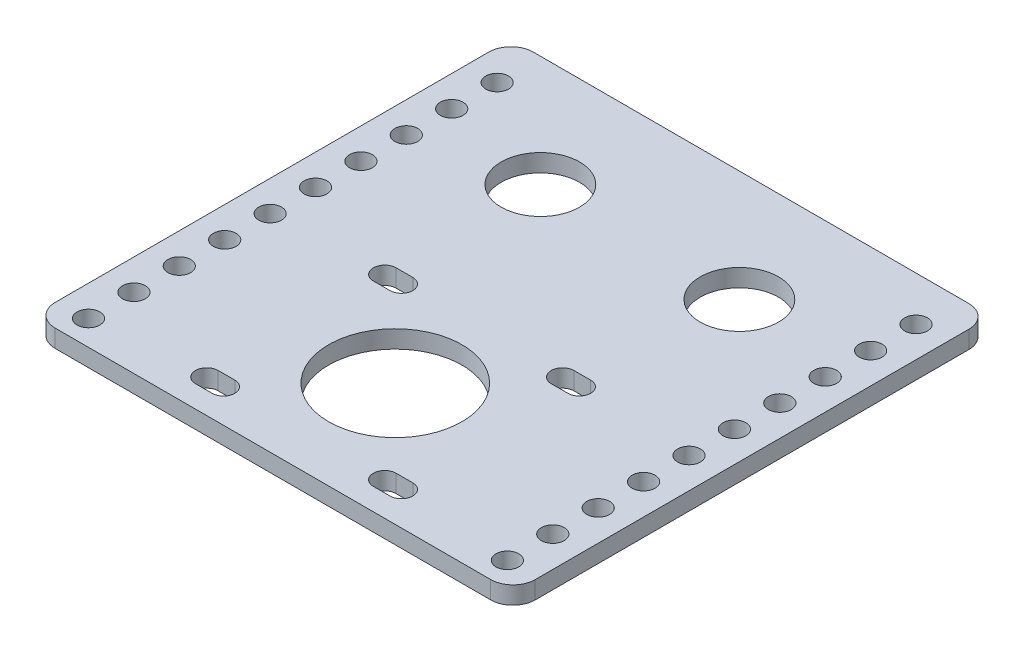
SolidWorks part; units mm, degrees
ref_plane "Front Plane" through (0, 0, 0) normal (0, 0, 1) x (1, 0, 0)
ref_plane "Top Plane" through (0, 0, 0) normal (0, 1, 0) x (1, 0, 0)
ref_plane "Right Plane" through (0, 0, 0) normal (1, 0, 0) x (0, 0, -1)
sketch "Sketch1" plane through (0, 0, 0) normal (0, 1, 0) x (1, 0, 0)
  line L0 (0, 0) -> (0, -50000) construction
  line L1 (-43.175, 43) -> (43.175, 43)
  line L2 (-43.175, 43) -> (-43.175, -43)
  line L3 (-43.175, -43) -> (43.175, -43)
  line L4 (43.175, 43) -> (43.175, -43)
  line L5 (-43.175, 43) -> (43.175, -43) construction
  line L6 (-43.175, -43) -> (43.175, 43) construction
  line L7 (37.675, 1.2802) -> (37.675, -49998.7198) construction
  line L8 (26.7767, 35) -> (-49973.2233, 35) construction
  circle A0 centre (37.675, 35) radius 2.05
  circle A1 centre (37.675, 26.8327) radius 2.05
  circle A2 centre (37.675, 18.6653) radius 2.05
  circle A3 centre (37.675, 10.498) radius 2.05
  circle A4 centre (37.675, 2.3306) radius 2.05
  circle A5 centre (37.675, -5.8367) radius 2.05
  circle A6 centre (37.675, -14.004) radius 2.05
  circle A7 centre (37.675, -22.1714) radius 2.05
  circle A8 centre (37.675, -30.3387) radius 2.05
  circle A9 centre (37.675, -38.506) radius 2.05
  circle A10 centre (-37.675, -38.506) radius 2.05
  circle A11 centre (-37.675, -30.3387) radius 2.05
  circle A12 centre (-37.675, -22.1714) radius 2.05
  circle A13 centre (-37.675, -14.004) radius 2.05
  circle A14 centre (-37.675, -5.8367) radius 2.05
  circle A15 centre (-37.675, 2.3306) radius 2.05
  circle A16 centre (-37.675, 10.498) radius 2.05
  circle A17 centre (-37.675, 18.6653) radius 2.05
  circle A18 centre (-37.675, 26.8327) radius 2.05
  circle A19 centre (-37.675, 35) radius 2.05
  point P0 (0, 0)
  dimension "D5" = 4.1
  dimension "D1" = 86
  dimension "D2" = 86.35
  dimension "D3" = 5.5
  dimension "D4" = 8
  dimension "D6" = 10
extrude "Boss-Extrude1" add sketch "Sketch1" along normal blind 3.175
fillet "Fillet1" radius 4 4 edges at (-43.175, 1.5875, -43) (43.175, 1.5875, -43) (43.175, 1.5875, 43) (-43.175, 1.5875, 43)
sketch "Sketch2" plane through (0, 3.175, 0) normal (0, 1, 0) x (1, 0, 0)
  line L0 (0, 0) -> (0, -50000) construction
  line L1 (0, 0) -> (50000, 0) construction
  line L2 (20.2816, 23) -> (50020.2816, 23) construction
  line L3 (39.175, 43) -> (-39.175, 43) construction
  line L4 (-17.6916, -13.7951) -> (0.2084, 30.1984) construction
  line L5 (35.5916, 15.8016) -> (17.6916, -28.1918) construction
  line L6 (0, -20.9934) -> (50000, -20.9934) construction
  line L7 (-16, -4.9934) -> (16, -4.9934) construction
  line L8 (-16, -4.9934) -> (-16, -36.9934) construction
  line L9 (-16, -36.9934) -> (16, -36.9934) construction
  line L10 (16, -4.9934) -> (16, -36.9934) construction
  line L11 (-16, -4.9934) -> (16, -36.9934) construction
  line L12 (-16, -36.9934) -> (16, -4.9934) construction
  line L13 (-10.05, -30.9934) -> (30.25, -30.9934) construction
  line L14 (-10.05, -30.9934) -> (-10.05, -10.9934) construction
  line L15 (-10.05, -10.9934) -> (30.25, -10.9934) construction
  line L16 (30.25, -30.9934) -> (30.25, -10.9934) construction
  line L17 (-10.05, -30.9934) -> (30.25, -10.9934) construction
  line L18 (-10.05, -10.9934) -> (30.25, -30.9934) construction
  line L19 (0, -10.9934) -> (0, -30.9934) construction
  line L20 (-17.9, -7.0434) -> (-14.9, -7.0434)
  line L21 (41.6, -0.9934) -> (-21.4, -0.9934) construction
  line L22 (41.6, -0.9934) -> (41.6, -40.9934) construction
  line L23 (41.6, -40.9934) -> (-21.4, -40.9934) construction
  line L24 (-21.4, -0.9934) -> (-21.4, -40.9934) construction
  line L25 (41.6, -0.9934) -> (-21.4, -40.9934) construction
  line L26 (41.6, -40.9934) -> (-21.4, -0.9934) construction
  line L27 (38.1, -4.9934) -> (-17.9, -4.9934) construction
  line L28 (38.1, -4.9934) -> (38.1, -36.9934) construction
  line L29 (38.1, -36.9934) -> (-17.9, -36.9934) construction
  line L30 (-17.9, -4.9934) -> (-17.9, -36.9934) construction
  line L31 (38.1, -4.9934) -> (-17.9, -36.9934) construction
  line L32 (38.1, -36.9934) -> (-17.9, -4.9934) construction
  line L33 (-14.9, -2.9434) -> (-17.9, -2.9434)
  line L34 (-6.9, -2.9434) -> (-9.9, -2.9434) construction
  line L35 (-9.9, -7.0434) -> (-6.9, -7.0434) construction
  line L36 (1.1, -2.9434) -> (-1.9, -2.9434) construction
  line L37 (-1.9, -7.0434) -> (1.1, -7.0434) construction
  line L38 (9.1, -2.9434) -> (6.1, -2.9434) construction
  line L39 (6.1, -7.0434) -> (9.1, -7.0434) construction
  line L40 (17.1, -2.9434) -> (14.1, -2.9434)
  line L41 (14.1, -7.0434) -> (17.1, -7.0434)
  line L42 (25.1, -2.9434) -> (22.1, -2.9434) construction
  line L43 (22.1, -7.0434) -> (25.1, -7.0434) construction
  line L44 (33.1, -2.9434) -> (30.1, -2.9434) construction
  line L45 (30.1, -7.0434) -> (33.1, -7.0434) construction
  line L46 (-14.9, -7.0434) -> (-6.9, -7.0434) construction
  line L47 (30.1, -34.9434) -> (33.1, -34.9434) construction
  line L48 (33.1, -39.0434) -> (30.1, -39.0434) construction
  line L49 (14.1, -34.9434) -> (17.1, -34.9434)
  line L50 (17.1, -39.0434) -> (14.1, -39.0434)
  line L51 (-17.9, -34.9434) -> (-14.9, -34.9434)
  line L52 (-14.9, -39.0434) -> (-17.9, -39.0434)
  circle A1 centre (-17.9, 23) radius 18 construction
  circle A3 centre (0, -20.9934) radius 19.1 construction
  circle A4 centre (17.9, 23) radius 19.1 construction
  arc A6 (-17.6916, -13.7951) -> (17.6916, -28.1918) centre (0, -20.9934) ccw construction
  arc A7 (0.2084, 30.1984) -> (35.5916, 15.8016) centre (17.9, 23) cw construction
  circle A8 centre (-17.9, 23) radius 7.05
  circle A9 centre (17.9, 23) radius 7.05
  circle A11 centre (-16, -4.9934) radius 2.05 construction
  circle A12 centre (16, -4.9934) radius 2.05 construction
  circle A13 centre (16, -36.9934) radius 2.05 construction
  circle A14 centre (-16, -36.9934) radius 2.05 construction
  circle A15 centre (0, -20.9934) radius 12
  arc A16 (-17.9, -2.9434) -> (-17.9, -7.0434) centre (-17.9, -4.9934) ccw
  circle A17 centre (38.1, -4.9934) radius 2.05 construction
  circle A18 centre (-17.9, -36.9934) radius 2.05 construction
  circle A19 centre (38.1, -36.9934) radius 2.05 construction
  arc A21 (-14.9, -7.0434) -> (-14.9, -2.9434) centre (-14.9, -4.9934) ccw
  arc A22 (-6.9, -7.0434) -> (-6.9, -2.9434) centre (-6.9, -4.9934) ccw construction
  arc A23 (-9.9, -2.9434) -> (-9.9, -7.0434) centre (-9.9, -4.9934) ccw construction
  arc A24 (1.1, -7.0434) -> (1.1, -2.9434) centre (1.1, -4.9934) ccw construction
  arc A25 (-1.9, -2.9434) -> (-1.9, -7.0434) centre (-1.9, -4.9934) ccw construction
  arc A26 (9.1, -7.0434) -> (9.1, -2.9434) centre (9.1, -4.9934) ccw construction
  arc A27 (6.1, -2.9434) -> (6.1, -7.0434) centre (6.1, -4.9934) ccw construction
  arc A28 (17.1, -7.0434) -> (17.1, -2.9434) centre (17.1, -4.9934) ccw
  arc A29 (14.1, -2.9434) -> (14.1, -7.0434) centre (14.1, -4.9934) ccw
  arc A30 (25.1, -7.0434) -> (25.1, -2.9434) centre (25.1, -4.9934) ccw construction
  arc A31 (22.1, -2.9434) -> (22.1, -7.0434) centre (22.1, -4.9934) ccw construction
  arc A32 (33.1, -7.0434) -> (33.1, -2.9434) centre (33.1, -4.9934) ccw construction
  arc A33 (30.1, -2.9434) -> (30.1, -7.0434) centre (30.1, -4.9934) ccw construction
  arc A34 (33.1, -34.9434) -> (33.1, -39.0434) centre (33.1, -36.9934) cw construction
  arc A35 (30.1, -39.0434) -> (30.1, -34.9434) centre (30.1, -36.9934) cw construction
  arc A36 (17.1, -34.9434) -> (17.1, -39.0434) centre (17.1, -36.9934) cw
  arc A37 (14.1, -39.0434) -> (14.1, -34.9434) centre (14.1, -36.9934) cw
  arc A38 (-17.9, -39.0434) -> (-17.9, -34.9434) centre (-17.9, -36.9934) cw
  arc A39 (-14.9, -34.9434) -> (-14.9, -39.0434) centre (-14.9, -36.9934) cw
  point P31 (10.1, -20.9934)
  point P36 (10.1, -20.9934)
  point P45 (10.1, -20.9934)
  dimension "D1" = 38.2
  dimension "D4" = 36
  dimension "D7" = 14.1
  dimension "D10" = 4.1
  dimension "D11" = 24
  dimension "D19" = 4.1
  dimension "D21" = 2.05
  dimension "D2" = 35.8
  dimension "D3" = 17.9
  dimension "D5" = 20
  dimension "D8" = 32
  dimension "D9" = 32
  dimension "D12" = 40.3
  dimension "D13" = 20
  dimension "D14" = 10.05
  dimension "D15" = 63
  dimension "D16" = 40
  dimension "D17" = 56
  dimension "D18" = 32
  dimension "D20" = 3
  dimension "D23" = 8
  dimension "D22" = 7
extrude "Cut-Extrude1" cut sketch "Sketch2" against normal blind 3.18
equation "\"w\"= 86.35mm"
equation "\"h\"= 86mm"
equation "\"D1@Sketch1\"=\"h\""
equation "\"D2@Sketch1\"=\"w\""
equation "\"sh\"= 4.1mm"
equation "\"D5@Sketch1\"=\"sh\""
equation "\"thick\"= 3.175mm"
equation "\"D1@Boss-Extrude1\"=\"thick\""
equation "\"ptich diameter\"= 38.2mm"
equation "\"gearC2C\"= 35.8mm"
equation "\"D1@Sketch2\"=\"ptich diameter\""
equation "\"D2@Sketch2\"=\"gearC2C\""
equation "\"D3@Sketch2\"=\"gearC2C\"/2"
equation "\"45 Tooth Hub-Mount Gear\" = 36mm"
equation "\"D4@Sketch2\"=\"45 Tooth Hub-Mount Gear\""
equation "\"pathLength\"= 215mm"
equation "\"D6@Sketch2\"=\"pathLength\""
equation "\"bearingID\"= 14.1mm"
equation "\"D7@Sketch2\"=\"bearingID\""
equation "\"pillowMountHoles\"= 32mm"
equation "\"D8@Sketch2\"=\"pillowMountHoles\""
equation "\"D9@Sketch2\"=\"pillowMountHoles\""
equation "\"D10@Sketch2\"=\"sh\""
equation "\"servow\"= 40.3mm"
equation "\"servoh\"= 20mm"
equation "\"D12@Sketch2\"=\"servow\""
equation "\"D13@Sketch2\"=\"servoh\""
equation "\"servoMountW\"= 63mm"
equation "\"servoMountH\"= 40mm"
equation "\"D15@Sketch2\"=\"servoMountW\""
equation "\"D16@Sketch2\"=\"servoMountH\""
equation "\"servoMountHoleW\"= \"servoMountW\" - 7mm"
equation "\"servoMountHoleH\"= \"servoMountH\" - 8mm"
equation "\"D17@Sketch2\"=\"servoMountHoleW\""
equation "\"D18@Sketch2\"=\"servoMountHoleH\""
equation "\"D19@Sketch2\"=\"sh\""
equation "\"D21@Sketch2\"=\"sh\"/2"
